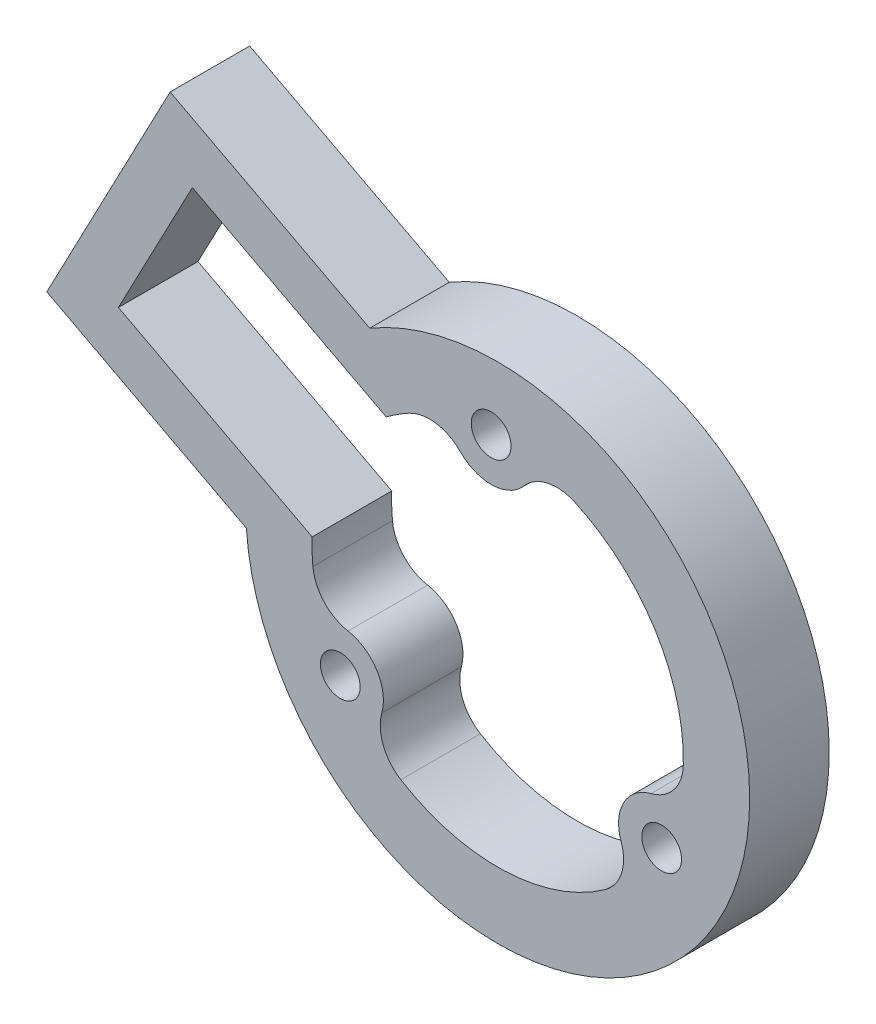
SolidWorks part; units mm, degrees
ref_plane "Plan de face" through (0, 0, 0) normal (0, 0, 1) x (1, 0, 0)
ref_plane "Plan de dessus" through (0, 0, 0) normal (0, 1, 0) x (1, 0, 0)
ref_plane "Plan de droite" through (0, 0, 0) normal (1, 0, 0) x (0, 0, -1)
sketch "Esquisse1" plane through (0, 0, 0) normal (0, 0, 1) x (1, 0, 0)
  line L0 (-0.4938, 13.9913) -> (-11.8699, -7.4233) construction
  line L1 (-11.8699, -7.4233) -> (12.3637, -6.568) construction
  line L2 (12.3637, -6.568) -> (-0.4938, 13.9913) construction
  line L3 (-9.6524, 16.3656) -> (-18.9527, -1.3405) construction
  line L7 (-9.6524, 16.3656) -> (-24.7026, 24.2708)
  line L9 (-18.9527, -1.3405) -> (-34.0028, 6.5647)
  line L11 (-24.7026, 24.2708) -> (-34.0028, 6.5647)
  line L12 (-11.5124, 12.8243) -> (-23.0214, 18.8695)
  line L13 (-23.0214, 18.8695) -> (-28.6015, 8.2459)
  line L14 (-28.6015, 8.2459) -> (-17.0926, 2.2007)
  line L15 (-11.5124, 12.8243) -> (-8.4082, 11.1938)
  line L16 (-17.0926, 2.2007) -> (-13.9884, 0.5702)
  arc A0 (-18.9527, -1.3405) -> (-9.6524, 16.3656) centre (0, 0) ccw
  circle A2 centre (-0.4938, 13.9913) radius 1.5
  arc A12 (-2.8156, 11.7171) -> (1.9825, 11.8865) centre (-0.4938, 13.9913) ccw
  arc A16 (5.8069, 12.7389) -> (1.9825, 11.8865) centre (4.4589, 9.7817) ccw
  arc A17 (-2.8156, 11.7171) -> (-6.6905, 12.2978) centre (-5.1374, 9.443) ccw
  arc A18 (-6.6905, 12.2978) -> (-8.4082, 11.1938) centre (0, 0) ccw
  arc A19 (8.1288, -11.3984) -> (9.3027, -7.6602) centre (6.2417, -8.7523) ccw
  arc A20 (11.5551, -3.4202) -> (9.3027, -7.6602) centre (12.3637, -6.568) ccw
  arc A21 (11.5551, -3.4202) -> (13.9955, -0.3547) centre (10.7465, -0.2724) ccw
  circle A22 centre (12.3637, -6.568) radius 1.5
  arc A23 (-13.9357, -1.3405) -> (-11.2853, -4.2263) centre (-10.7006, -1.0293) ccw
  arc A24 (-8.7395, -8.2969) -> (-11.2853, -4.2263) centre (-11.8699, -7.4233) ccw
  arc A25 (-8.7395, -8.2969) -> (-7.305, -11.9431) centre (-5.6092, -9.1706) ccw
  circle A26 centre (-11.8699, -7.4233) radius 1.5
  arc A27 (-7.305, -11.9431) -> (8.1288, -11.3984) centre (0, 0) ccw
  arc A28 (13.9955, -0.3547) -> (5.8069, 12.7389) centre (0, 0) ccw
  circle A29 centre (-0.4938, 13.9913) radius 3.25 construction
  arc A30 (-13.9884, 0.5702) -> (-13.9357, -1.3405) centre (0, 0) ccw
  point P1 (-14.3025, 7.5125)
  point P31 (0, 0)
  point P33 (-11.5124, 12.8243)
  point P36 (-17.0926, 2.2007)
  dimension "D1" = 38
  dimension "D2" = 3
  dimension "D3" = 3
  dimension "D4" = 6.5
  dimension "D5" = 14
  dimension "D8" = 14
  dimension "D9" = 14
  dimension "D10" = 14
  dimension "D11" = 3.25
  dimension "D12" = 3.25
  dimension "D13" = 10.75
  dimension "D6" = 60
  dimension "D7" = 60
  dimension "D14" = 10.75
  dimension "D15" = 20
  dimension "D16" = 17
  dimension "D17" = 17
  dimension "D18" = 90
  dimension "D19" = 90
  dimension "D20" = 6
  dimension "D21" = 6
  dimension "D22" = 90
  dimension "D23" = 90
  dimension "D24" = 13
  dimension "D25" = 90
extrude "Boss.-Extru.2" add sketch "Esquisse1" along normal blind 6
sketch "Esquisse2" plane through (0, 0, 6) normal (0, 0, 1) x (1, 0, 0)
